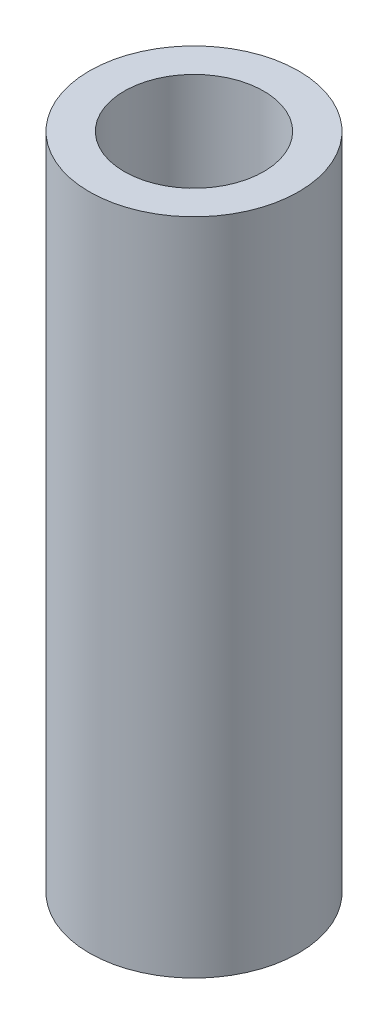
SolidWorks part; units mm, degrees
material "Fr-4"
ref_plane "Front Plane" through (0, 0, 0) normal (0, 0, 1) x (1, 0, 0)
ref_plane "Top Plane" through (0, 0, 0) normal (0, 1, 0) x (1, 0, 0)
ref_plane "Right Plane" through (0, 0, 0) normal (1, 0, 0) x (0, 0, -1)
sketch "Sketch1" plane through (0, 0, 0) normal (0, 1, 0) x (1, 0, 0)
  circle A0 centre (0, 0) radius 4.7625
  circle A1 centre (0, 0) radius 3.175
  dimension "D1" = 9.525
  dimension "D2" = 6.35
extrude "Boss-Extrude1" add sketch "Sketch1" along normal blind 30
ref_plane "Plane1" through (0, 0, 0) normal (0, -1, 0) x (-1, 0, 0)
sketch "Sketch2" plane through (0, 0, 0) normal (0, -1, 0) x (-1, 0, 0)
  point P0 (0, 0)
ref_plane "Plane2" through (0, 30, 0) normal (0, 1, 0) x (1, 0, 0)
sketch "Sketch4" plane through (0, 30, 0) normal (0, 1, 0) x (1, 0, 0)
  point P0 (0, 0)
